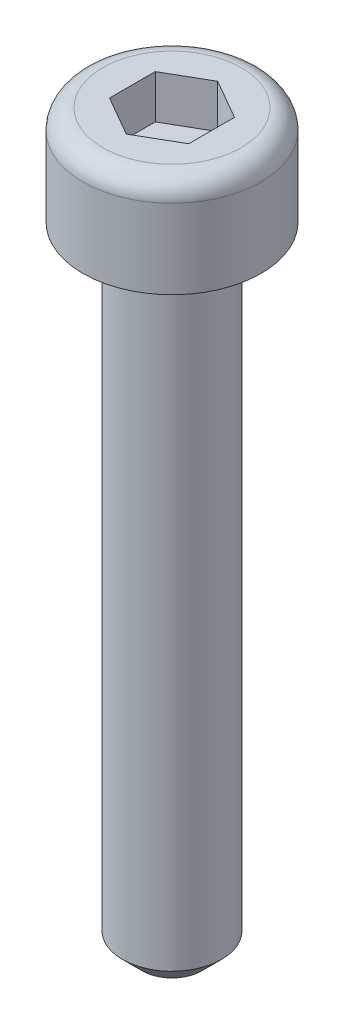
SolidWorks part; units mm, degrees
material "acero"
ref_plane "Alzado" through (0, 0, 0) normal (0, 0, 1) x (1, 0, 0)
ref_plane "Planta" through (0, 0, 0) normal (0, 1, 0) x (1, 0, 0)
ref_plane "Vista lateral" through (0, 0, 0) normal (1, 0, 0) x (0, 0, -1)
sketch "Croquis1" plane through (0, 0, 0) normal (0, 0, 1) x (1, 0, 0)
  line L0 (0, 0) -> (0, -60.9498) construction
  line L1 (0, 0) -> (2.25, 0)
  line L2 (2.25, 0) -> (2.25, -2.5)
  line L3 (2.25, -2.5) -> (1.25, -2.5)
  line L4 (1.25, -2.5) -> (1.25, -18.5)
  line L5 (1.25, -18.5) -> (0, -18.5)
  line L6 (0, -18.5) -> (0, 0)
  dimension "D1" = 16
  dimension "D2" = 2.5
  dimension "D3" = 4.5
  dimension "D4" = 2.5
revolve "Revolución1" add sketch "Croquis1" angle 360 about L0
sketch "Croquis2" plane through (0, 0, 0) normal (0, 1, 0) x (1, 0, 0)
  line L1 (1, 0.5774) -> (0, 1.1547)
  line L2 (0, 1.1547) -> (-1, 0.5774)
  line L3 (-1, 0.5774) -> (-1, -0.5774)
  line L4 (-1, -0.5774) -> (0, -1.1547)
  line L5 (0, -1.1547) -> (1, -0.5774)
  line L6 (1, -0.5774) -> (1, 0.5774)
  circle A0 centre (0, 0) radius 1 construction
  dimension "D1" = 2
extrude "Cortar-Extruir1" cut sketch "Croquis2" against normal blind 1.1
chamfer "Chaflán1" distance 0.5 angle 45 1 edges at (0, -18.5, 1.25)
fillet "Redondeo1" radius 0.5 1 edges at (0, 0, 2.25)
